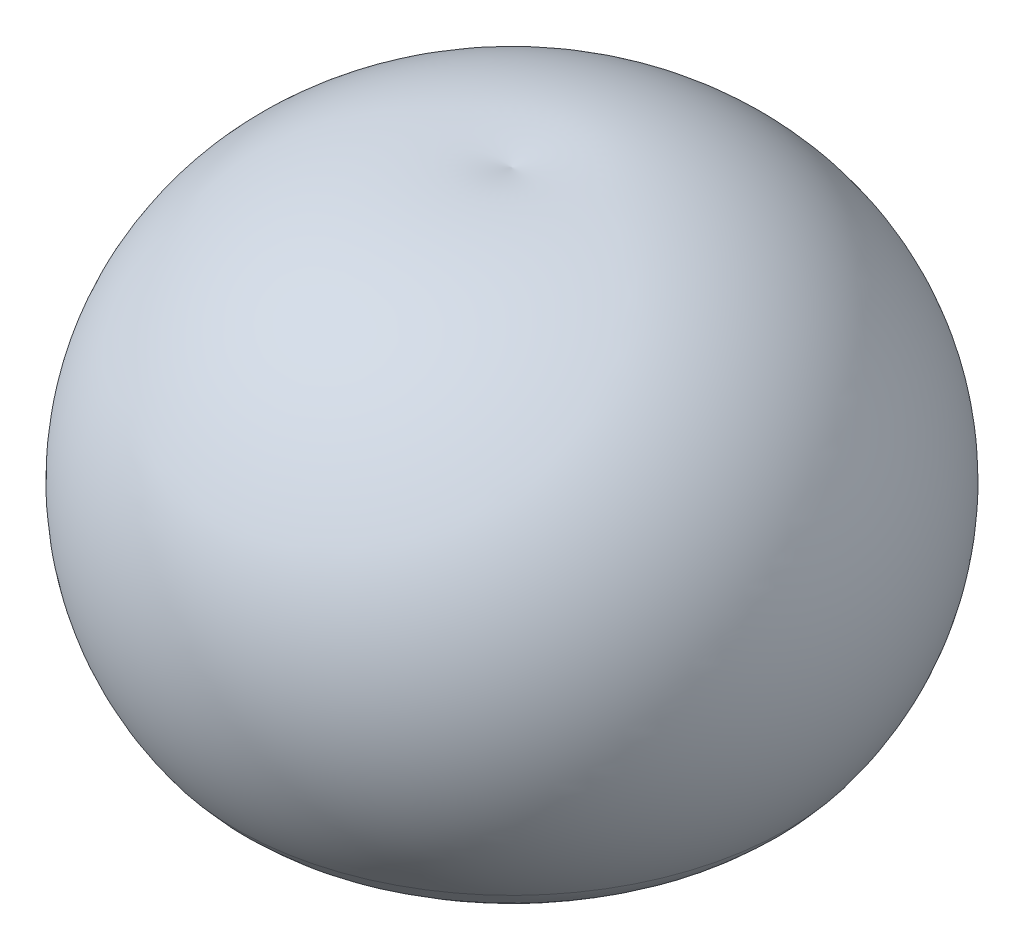
SolidWorks part; units mm, degrees
ref_plane "Front Plane" through (0, 0, 0) normal (0, 0, 1) x (1, 0, 0)
ref_plane "Top Plane" through (0, 0, 0) normal (0, 1, 0) x (1, 0, 0)
ref_plane "Right Plane" through (0, 0, 0) normal (1, 0, 0) x (0, 0, -1)
sketch "Sketch1" plane through (0, 0, 0) normal (0, 0, 1) x (1, 0, 0)
  line L0 (0, 0) -> (260, 675)
  line L1 (260, 675) -> (940, 675)
  line L2 (940, 675) -> (940, 640)
  line L3 (940, 640) -> (1615, 640)
  line L4 (940, 675) -> (1615, 640)
  line L5 (940, 675) -> (317.971, 410.5573)
  line L6 (940, 675) -> (532.9299, 1214.5776)
  line L7 (260, 675) -> (-356.2893, 962.3804)
  line L8 (260, 675) -> (817.0234, 284.968)
  line L9 (260, 675) -> (817.0234, 284.968) construction
  line L10 (817.0234, 284.968) -> (796.9482, 256.2977) construction
  line L11 (796.9482, 256.2977) -> (1349.8758, -130.8664) construction
  line L12 (817.0234, 284.968) -> (1349.8758, -130.8664)
  line L13 (260, 675) -> (-356.2893, 962.3804) construction
  line L14 (-356.2893, 962.3804) -> (-341.4977, 994.1012) construction
  line L15 (-341.4977, 994.1012) -> (-953.2554, 1279.3685) construction
  line L16 (-953.2554, 1279.3685) -> (-356.2893, 962.3804)
  line L17 (817.0234, 284.968) -> (155.809, 425.1304)
  line L18 (-356.2893, 962.3804) -> (-215.3938, 301.3218)
  line L19 (-356.2893, 962.3804) -> (319.2187, 939.1661)
  arc A0 (-356.2893, 962.3804) -> (817.0234, 284.968) centre (260, 675) cw
  arc A1 (-953.2554, 1279.3685) -> (1349.8758, -130.8664) centre (260, 675) cw
  arc A2 (1349.8758, -130.8664) -> (155.809, 425.1304) centre (817.0234, 284.968) cw
  arc A3 (-953.2554, 1279.3685) -> (-215.3938, 301.3218) centre (-356.2893, 962.3804) ccw
  arc A4 (155.809, 425.1304) -> (319.2187, 939.1661) centre (260, 675) ccw
  arc A5 (319.2187, 939.1661) -> (240.6768, 1279.3685) centre (-356.2893, 962.3804) ccw
  arc A6 (-215.3938, 301.3218) -> (240.6768, 1279.3685) centre (260, 675) cw
  dimension "D1" = 260
  dimension "D2" = 675
  dimension "D3" = 680
  dimension "D4" = 675
  dimension "D5" = 35
  dimension "D6" = 675.9068
  dimension "D7" = 154
  dimension "130" = 130
  dimension "D9" = 35
  dimension "D10" = 155
  dimension "D8" = 154
  dimension "D11" = 130
  dimension "D12" = 154
sketch "Sketch2" plane through (0, 0, 0) normal (0, 0, 1) x (1, 0, 0)
  arc A0 (1349.8758, -130.8664) -> (-953.2554, 1279.3685) centre (260, 675) ccw construction
  arc A1 (-953.2554, 1279.3685) -> (-215.3938, 301.3218) centre (-356.2893, 962.3804) ccw construction
  arc A2 (240.6768, 1279.3685) -> (-215.3938, 301.3218) centre (260, 675) ccw construction
  arc A3 (319.2187, 939.1661) -> (240.6768, 1279.3685) centre (-356.2893, 962.3804) ccw construction
  arc A4 (155.809, 425.1304) -> (319.2187, 939.1661) centre (260, 675) ccw construction
  arc A5 (155.809, 425.1304) -> (1349.8758, -130.8664) centre (817.0234, 284.968) ccw construction
  arc A6 (1349.8758, -130.8664) -> (-953.2554, 1279.3685) centre (260, 675) ccw
  arc A7 (-953.2554, 1279.3685) -> (-215.3938, 301.3218) centre (-356.2893, 962.3804) ccw
  arc A8 (240.6768, 1279.3685) -> (-215.3938, 301.3218) centre (260, 675) ccw
  arc A9 (319.2187, 939.1661) -> (240.6768, 1279.3685) centre (-356.2893, 962.3804) ccw
  arc A10 (155.809, 425.1304) -> (319.2187, 939.1661) centre (260, 675) ccw
  arc A11 (155.809, 425.1304) -> (1349.8758, -130.8664) centre (817.0234, 284.968) ccw
sketch "Sketch4" plane through (0, 0, 0) normal (0, 0, 1) x (1, 0, 0)
  line L0 (0, 1220.9255) -> (0, 2005.2819)
  arc A1 (240.6768, 1279.3685) -> (-215.3938, 301.3218) centre (260, 675) ccw construction
  arc A2 (1349.8758, -130.8664) -> (-953.2554, 1279.3685) centre (260, 675) ccw construction
  arc A3 (155.809, 425.1304) -> (1349.8758, -130.8664) centre (817.0234, 284.968) ccw construction
  arc A5 (1349.8758, -130.8664) -> (0, 2005.2819) centre (260, 675) ccw
  arc A6 (0, 1220.9255) -> (281.1001, 405.1012) centre (-260, 675) cw
  arc A9 (155.809, 425.1304) -> (319.2187, 939.1661) centre (260, 675) ccw construction
  arc A10 (155.809, 425.1304) -> (1349.8758, -130.8664) centre (817.0234, 284.968) ccw
  arc A11 (155.809, 425.1304) -> (281.1001, 405.1012) centre (260, 675) ccw
revolve "Revolve2" add sketch "Sketch4" angle 360 about L0
equation "\"D8@Sketch1\"=\"D7@Sketch1\""
equation "\"D12@Sketch1\"=\"D7@Sketch1\""
